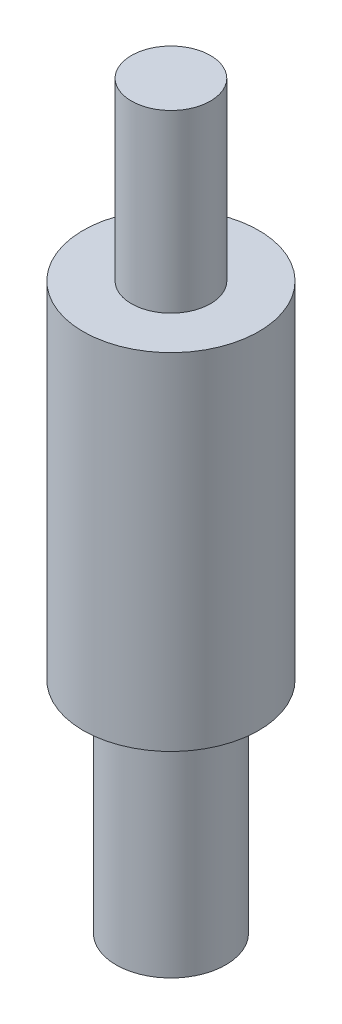
SolidWorks part; units mm, degrees
ref_plane "Front Plane" through (0, 0, 0) normal (0, 0, 1) x (1, 0, 0)
ref_plane "Top Plane" through (0, 0, 0) normal (0, 1, 0) x (1, 0, 0)
ref_plane "Right Plane" through (0, 0, 0) normal (1, 0, 0) x (0, 0, -1)
sketch "Sketch1" plane through (0, 0, 0) normal (0, 1, 0) x (1, 0, 0)
  circle A0 centre (0, 0) radius 1.25
  dimension "D1" = 2.5
extrude "Boss-Extrude1" add sketch "Sketch1" along normal blind 5
sketch "Sketch2" plane through (0, 5, 0) normal (0, 1, 0) x (1, 0, 0)
  circle A0 centre (0, 0) radius 2
  dimension "D1" = 4
extrude "Boss-Extrude2" add sketch "Sketch2" along normal blind 7.87
sketch "Sketch3" plane through (0, 12.87, 0) normal (0, 1, 0) x (1, 0, 0)
  circle A0 centre (0, 0) radius 0.9
  dimension "D1" = 1.8
extrude "Boss-Extrude3" add sketch "Sketch3" along normal blind 4
